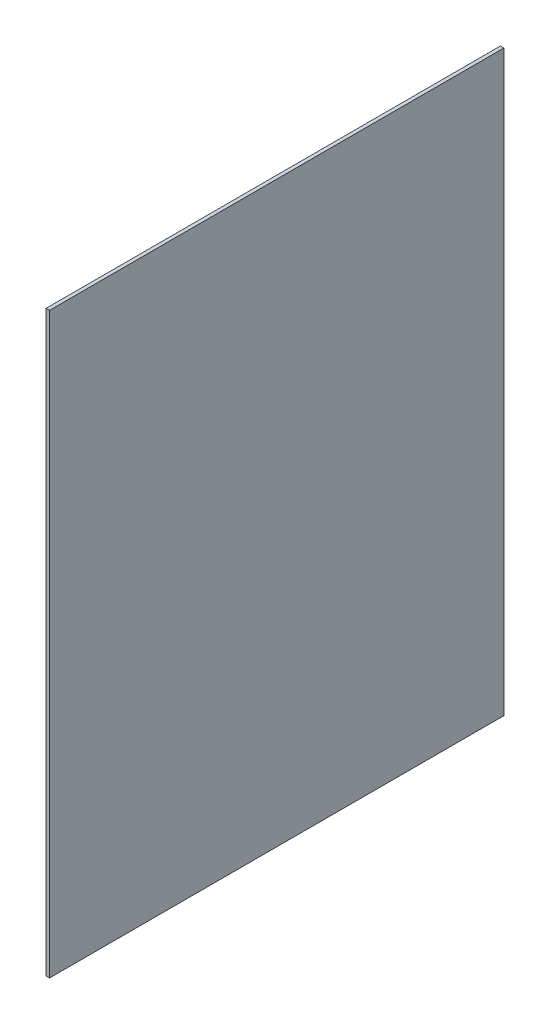
SolidWorks part; units mm, degrees
ref_plane "Front Plane" through (0, 0, 0) normal (0, 0, 1) x (1, 0, 0)
ref_plane "Top Plane" through (0, 0, 0) normal (0, 1, 0) x (1, 0, 0)
ref_plane "Right Plane" through (0, 0, 0) normal (1, 0, 0) x (0, 0, -1)
sketch "Sketch1" plane through (0, 0, 0) normal (1, 0, 0) x (0, 0, -1)
  line L1 (0, 0) -> (1676.4, 0)
  line L2 (0, 0) -> (0, 2133.6)
  line L3 (0, 2133.6) -> (1676.4, 2133.6)
  line L4 (1676.4, 0) -> (1676.4, 2133.6)
  dimension "D1" = 1676.4
  dimension "D2" = 2133.6
extrude "Boss-Extrude1" add sketch "Sketch1" along normal blind 12.7
